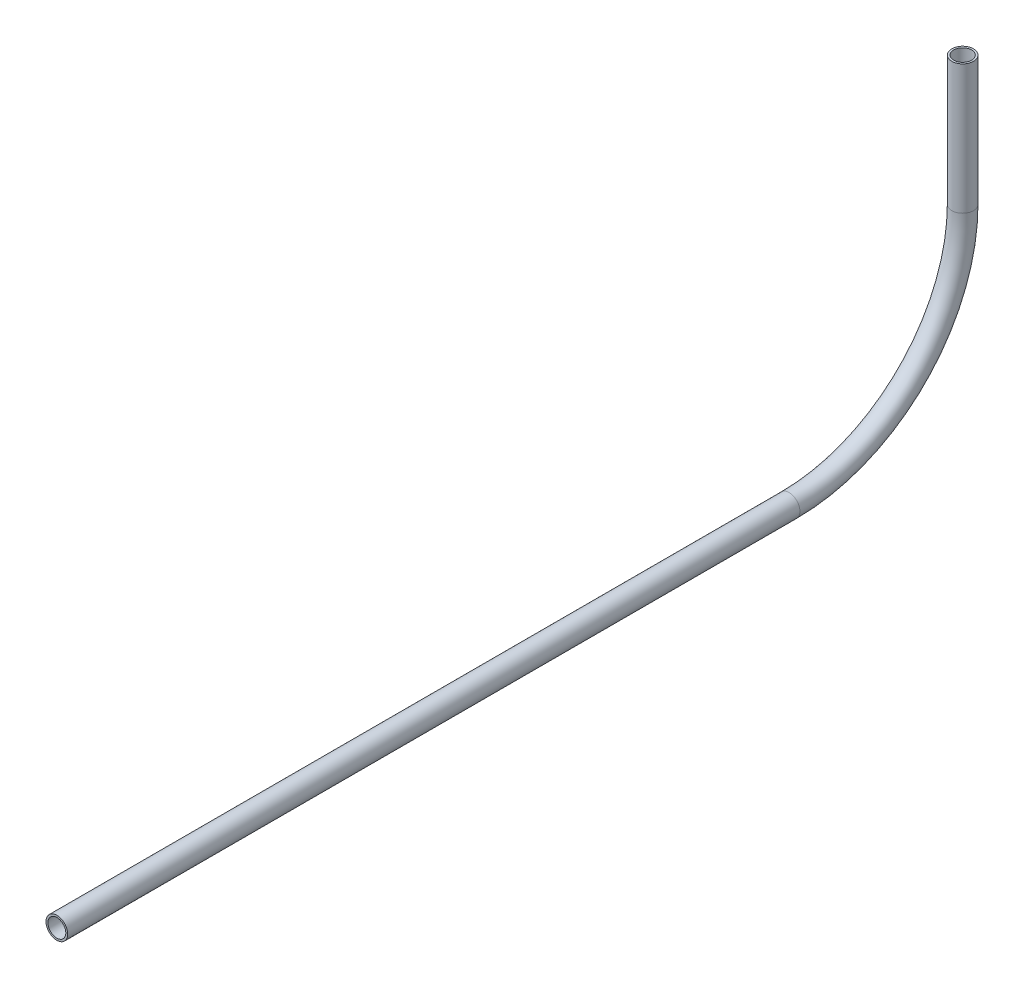
SolidWorks part; units mm, degrees
ref_plane "Front Plane" through (0, 0, 0) normal (0, 0, 1) x (1, 0, 0)
ref_plane "Top Plane" through (0, 0, 0) normal (0, 1, 0) x (1, 0, 0)
ref_plane "Right Plane" through (0, 0, 0) normal (1, 0, 0) x (0, 0, -1)
sketch "Sketch1" plane through (0, 0, 0) normal (1, 0, 0) x (0, 0, -1)
  line L0 (-271.4926, 163.432) -> (-57.1906, 163.432)
  line L1 (-6.3906, 214.232) -> (-6.3906, 252.087)
  line L2 (-9.5656, 252.087) -> (-3.2156, 252.087) construction
  arc A0 (-57.1906, 163.432) -> (-6.3906, 214.232) centre (-57.1906, 214.232) ccw
  point P2 (-7.342, 252.087)
  dimension "D1" = 50.8
other "Pipe 0.5 SCH 40(1)"
ref_plane "Plane1" through (0, 163.432, 271.4926) normal (0, 0, -1) x (0, 1, 0)
sketch "Sketch11" plane through (0, 163.432, 271.4926) normal (0, 0, -1) x (0, 1, 0)
  circle A0 centre (0, 0) radius 3.175
  circle A1 centre (0, 0) radius 2.6162
  point P5 (0, 0)
  dimension "In_dia" = 6.35
  dimension "Out_dia" = 5.2324
